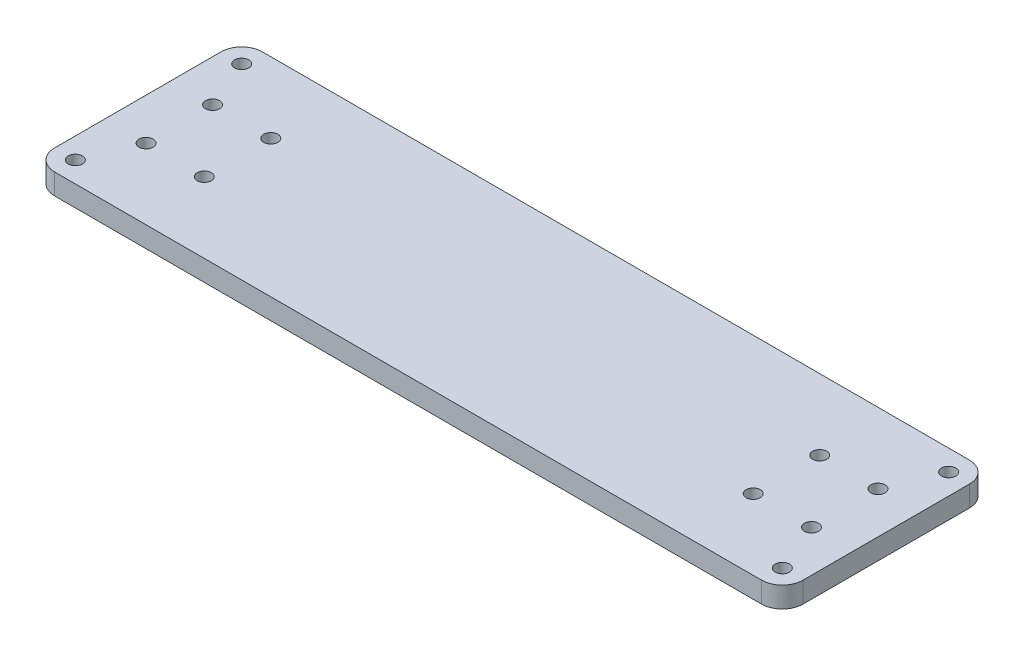
SolidWorks part; units mm, degrees
ref_plane "前视基准面" through (0, 0, 0) normal (0, 0, 1) x (1, 0, 0)
ref_plane "上视基准面" through (0, 0, 0) normal (0, 1, 0) x (1, 0, 0)
ref_plane "右视基准面" through (0, 0, 0) normal (1, 0, 0) x (0, 0, -1)
sketch "草图1" plane through (0, 0, 0) normal (0, 1, 0) x (1, 0, 0)
  line L0 (-73, -1000) -> (-73, 49000) construction
  line L1 (-85, 25) -> (85, 25)
  line L2 (-90, 20) -> (-90, -20)
  line L3 (-85, -25) -> (85, -25)
  line L4 (90, 20) -> (90, -20)
  line L5 (0, -25) -> (0, 25) construction
  line L6 (-90, 0) -> (90, 0) construction
  circle A1 centre (-85, 20) radius 1.7
  circle A2 centre (-85, -20) radius 1.7
  circle A3 centre (85, 20) radius 1.7
  circle A4 centre (85, -20) radius 1.7
  arc A5 (-90, -20) -> (-85, -25) centre (-85, -20) ccw
  arc A6 (85, -25) -> (90, -20) centre (85, -20) ccw
  arc A7 (85, 25) -> (90, 20) centre (85, 20) cw
  arc A8 (-85, 25) -> (-90, 20) centre (-85, 20) ccw
  circle A9 centre (-80, 8) radius 1.7
  circle A10 centre (-80, -8) radius 1.7
  circle A11 centre (-66, -8) radius 1.7
  circle A12 centre (-66, 8) radius 1.7
  circle A13 centre (66, -8) radius 1.7
  circle A14 centre (66, 8) radius 1.7
  circle A15 centre (80, -8) radius 1.7
  circle A16 centre (80, 8) radius 1.7
  point P0 (0, 0)
  point P18 (-90, -25)
  point P23 (90, 25)
  point P26 (-90, 25)
  dimension "D3" = 3.4
  dimension "D4" = 5
  dimension "D5" = 5
  dimension "D6" = 3.4
  dimension "D1" = 50
  dimension "D2" = 180
  dimension "D7" = 5
  dimension "D8" = 5
  dimension "D9" = 16
  dimension "D10" = 14
extrude "凸台-拉伸1" add sketch "草图1" along normal blind 5
